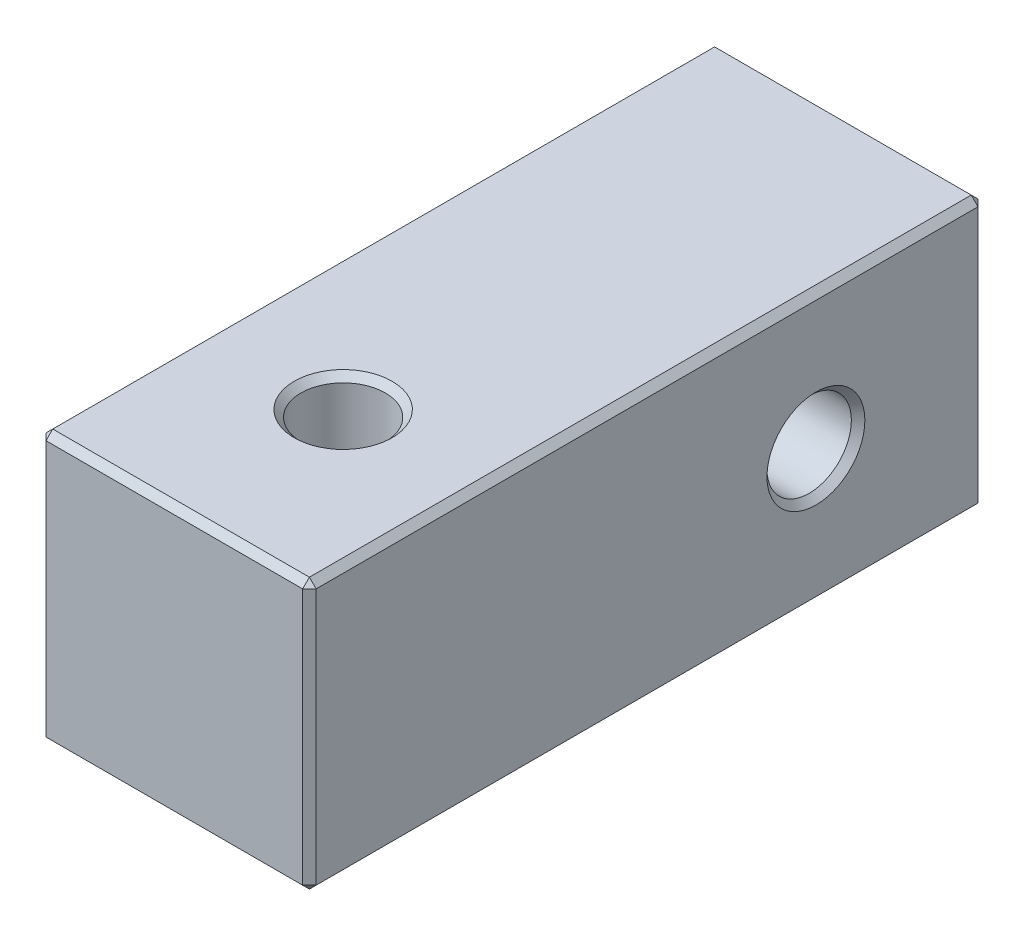
SolidWorks part; units mm, degrees
material "6061 合金"
ref_plane "前视基准面" through (0, 0, 0) normal (0, 0, 1) x (1, 0, 0)
ref_plane "上视基准面" through (0, 0, 0) normal (0, 1, 0) x (1, 0, 0)
ref_plane "右视基准面" through (0, 0, 0) normal (1, 0, 0) x (0, 0, -1)
sketch "草图1" plane through (0, 0, 0) normal (0, 0, 1) x (1, 0, 0)
  line L1 (-4, 4) -> (4, 4)
  line L2 (-4, 4) -> (-4, -4)
  line L3 (-4, -4) -> (4, -4)
  line L4 (4, 4) -> (4, -4)
  line L5 (-4, 4) -> (4, -4) construction
  line L6 (-4, -4) -> (4, 4) construction
  point P0 (0, 0)
  dimension "D1" = 8
extrude "凸台-拉伸1" add sketch "草图1" along normal mid plane 20
hole_wizard "M3 螺纹孔1" positions "草图2" profile "草图3" tap size "M3" standard "GB" end condition through all
sketch "草图2" plane through (4, 0, 0) normal (1, 0, 0) x (0, 0, -1)
  line L0 (0, 0) -> (50000, 0) construction
  line L1 (10, -4) -> (10, 4) construction
  point P0 (5, 0)
  dimension "D1" = 5
sketch "草图3" plane through (4, 0, -5) normal (0, 1, 0) x (0, 0, -1)
  line L0 (0, 0) -> (0, 8)
  line L1 (0, 8) -> (1.25, 8)
  line L2 (1.25, 8) -> (1.25, 0)
  line L5 (1.25, 0) -> (0, 0)
  line L11 (0, -6.35) -> (0, 107.95) construction
  dimension "通孔螺纹孔钻头直径" = 2.5
  dimension "通孔螺纹孔钻头深度" = 8
cosmetic thread "孔螺蚊线1" parameters "D2"=3
hole_wizard "M3 螺纹孔2" positions "草图4" profile "草图5" tap size "M3" standard "GB" end condition through all
sketch "草图4" plane through (0, 4, 0) normal (0, 1, 0) x (1, 0, 0)
  line L0 (4, -10) -> (-4, -10) construction
  line L1 (0, 0) -> (0, 50000) construction
  point P0 (0, -5)
  dimension "D1" = 5
sketch "草图5" plane through (0, 4, 5) normal (1, 0, 0) x (0, 0, 1)
  line L0 (0, 0) -> (0, 8)
  line L1 (0, 8) -> (1.25, 8)
  line L2 (1.25, 8) -> (1.25, 0)
  line L5 (1.25, 0) -> (0, 0)
  line L11 (0, -6.35) -> (0, 107.95) construction
  dimension "通孔螺纹孔钻头直径" = 2.5
  dimension "通孔螺纹孔钻头深度" = 8
cosmetic thread "孔螺蚊线2" parameters "D2"=3
chamfer "倒角1" distance 0.2 angle 45 16 edges at (0, -4, 6.25) (-4, 0, -6.25) (0, 4, 6.25) (0, -4, 10) (0, -4, -10) (-4, 0, 10) (-4, -4, 0) (-4, 0, -10) (0, 4, 10) (-4, 4, 0) (0, 4, -10) (4, -4, 0) (4, 0, 10) (4, 4, 0) (4, 0, -10) (4, 0, -6.25)
